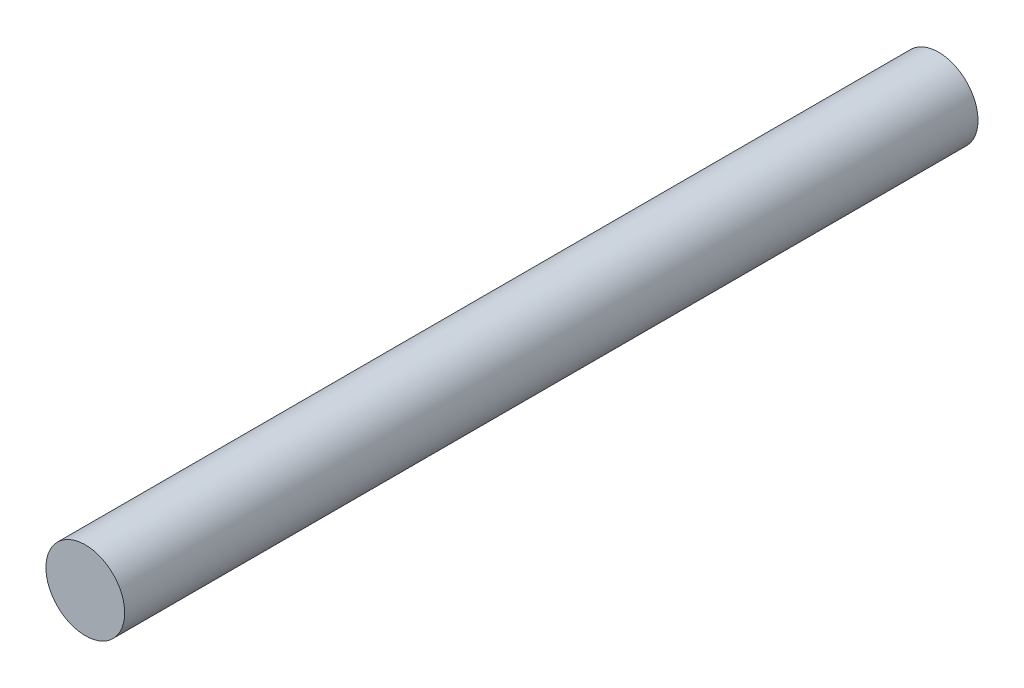
SolidWorks part; units mm, degrees
ref_plane "Front Plane" through (0, 0, 0) normal (0, 0, 1) x (1, 0, 0)
ref_plane "Top Plane" through (0, 0, 0) normal (0, 1, 0) x (1, 0, 0)
ref_plane "Right Plane" through (0, 0, 0) normal (1, 0, 0) x (0, 0, -1)
sketch "Sketch1" plane through (0, 0, 0) normal (0, 0, 1) x (1, 0, 0)
  circle A0 centre (0, 0) radius 3
  dimension "D1" = 6
extrude "Boss-Extrude1" add sketch "Sketch1" along normal mid plane 65
